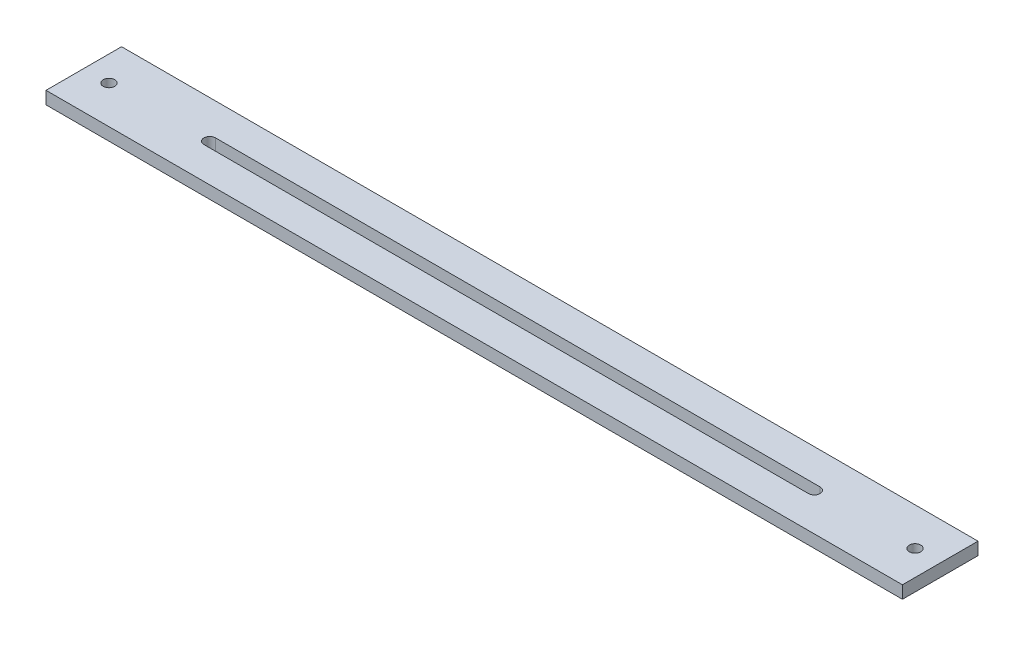
SolidWorks part; units mm, degrees
ref_plane "Front Plane" through (0, 0, 0) normal (0, 0, 1) x (1, 0, 0)
ref_plane "Top Plane" through (0, 0, 0) normal (0, 1, 0) x (1, 0, 0)
ref_plane "Right Plane" through (0, 0, 0) normal (1, 0, 0) x (0, 0, -1)
sketch "Sketch1" plane through (0, 0, 0) normal (0, 1, 0) x (1, 0, 0)
  line L1 (0, 0) -> (215.9, 0)
  line L2 (0, 0) -> (0, 19.05)
  line L3 (0, 19.05) -> (215.9, 19.05)
  line L4 (215.9, 0) -> (215.9, 19.05)
  dimension "D1" = 215.9
  dimension "D2" = 19.05
extrude "Boss-Extrude1" add sketch "Sketch1" along normal blind 3.175
sketch "Sketch3" plane through (0, 3.175, 0) normal (0, 1, 0) x (1, 0, 0)
  line L0 (0, 19.05) -> (0, 0) construction
  line L1 (0, 0) -> (215.9, 0) construction
  line L2 (215.9, 0) -> (215.9, 19.05) construction
  line L3 (31.75, 10.9855) -> (184.15, 10.9855)
  line L5 (31.75, 8.0645) -> (184.15, 8.0645)
  circle A0 centre (6.35, 9.525) radius 1.4605
  circle A1 centre (209.55, 9.525) radius 1.4605
  circle A2 centre (31.75, 9.525) radius 1.4605
  circle A3 centre (184.15, 9.525) radius 1.4605
  point P18 (0, 0)
  point P19 (0, 0)
  point P20 (0, 0)
  dimension "D1" = 6.35
  dimension "D2" = 2.921
  dimension "D4" = 2.921
  dimension "D5" = 6.35
  dimension "D6" = 9.525
  dimension "D7" = 2.921
  dimension "D8" = 25.4
  dimension "D9" = 9.525
  dimension "D10" = 2.921
  dimension "D11" = 25.4
  dimension "D12" = 9.525
  dimension "D3" = 9.525
  dimension "D13" = 152.4
  dimension "D14" = 1.4605
  dimension "D15" = 152.4
  dimension "D16" = 1.4605
extrude "Cut-Extrude5" cut sketch "Sketch3" against normal through all contours A3 L3 A2 L5 | A3 | A1 | A0
